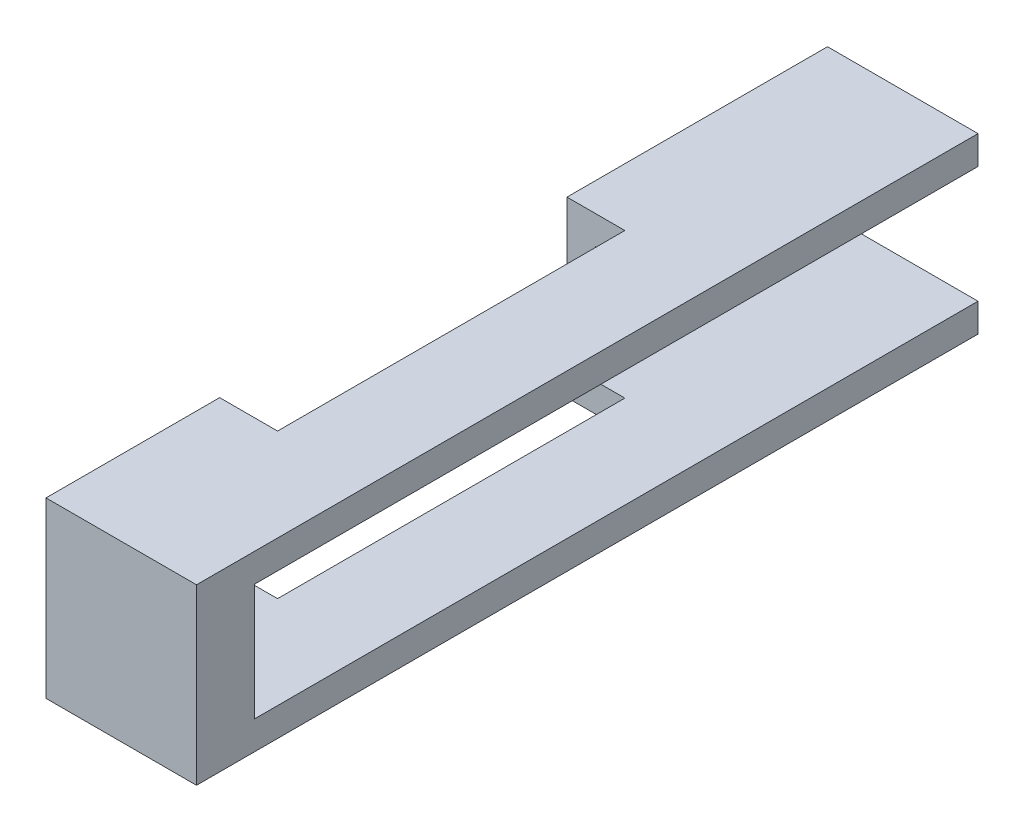
SolidWorks part; units mm, degrees
ref_plane "前视基准面" through (0, 0, 0) normal (0, 0, 1) x (1, 0, 0)
ref_plane "上视基准面" through (0, 0, 0) normal (0, 1, 0) x (1, 0, 0)
ref_plane "右视基准面" through (0, 0, 0) normal (1, 0, 0) x (0, 0, -1)
other "Configuration Table"
sketch "草图1" plane through (0, 0, 0) normal (0, 1, 0) x (1, 0, 0)
  line L1 (-15, 15) -> (15, 15)
  line L2 (-15, 15) -> (-15, -15)
  line L3 (-15, -15) -> (15, -15)
  line L4 (15, 15) -> (15, -15)
  line L5 (-15, 15) -> (15, -15) construction
  line L6 (-15, -15) -> (15, 15) construction
  point P0 (0, 0)
  dimension "D1" = 30
  dimension "D2" = 30
extrude "凸台-拉伸1" add sketch "草图1" along normal blind 30
sketch "草图2" plane through (15, 0, 0) normal (1, 0, 0) x (0, 0, -1)
  line L0 (15, 30) -> (15, 0) construction
  line L1 (-5, 4.975) -> (15, 4.975)
  line L2 (-5, 4.975) -> (-5, 25.025)
  line L3 (-5, 25.025) -> (15, 25.025)
  line L4 (15, 4.975) -> (15, 25.025)
  line L5 (-5, 4.975) -> (15, 25.025) construction
  line L6 (-5, 25.025) -> (15, 4.975) construction
  line L7 (-15, 15) -> (15, 15) construction
  line L9 (-15, 30) -> (-15, 0) construction
  point P0 (5, 15)
  dimension "D1" = 20.05
  dimension "D2" = 20
extrude "切除-拉伸1" cut sketch "草图2" against normal blind 20
sketch "草图3" plane through (-5, 0, 0) normal (1, 0, 0) x (0, 0, -1)
  line L0 (-5, 25.025) -> (15, 4.975)
  line L1 (15, 25.025) -> (-5, 4.975)
  circle A0 centre (5, 15) radius 3.1
  dimension "D1" = 6.2
extrude "切除-拉伸2" cut sketch "草图3" against normal blind 20 contours L0 A0 L1 | L1 A0 L0 | L0 A0 L1 | L1 A0 L0
sketch "草图4" plane through (0, 0, 0) normal (0, -1, 0) x (1, 0, 0)
  line L0 (-10, -15) -> (-10, 15)
  line L4 (15, -15) -> (15, 15)
  line L5 (15, 15) -> (-15, 15)
  line L6 (-15, 15) -> (-15, -15)
  line L7 (-15, -15) -> (15, -15)
  line L8 (15, -15) -> (15, 15)
  line L9 (15, 15) -> (-15, 15)
  line L10 (-15, 15) -> (-15, -15)
  line L11 (-15, -15) -> (15, -15)
  line M7 (15, 15) -> (-15, 15)
  line M8 (-15, 15) -> (-15, -15)
  line M9 (-15, -15) -> (15, -15)
  dimension "D2" = 5
  dimension "D1" = 0
extrude "切除-拉伸3" cut sketch "草图4" against normal blind 55 contours L0 M9 M7 M8
sketch "草图5" plane through (0, 0, -15) normal (0, 0, -1) x (-1, 0, 0)
  line L0 (-15, 30) -> (10, 30) construction
  line L1 (-15, 30) -> (0, 30)
  line L2 (-15, 30) -> (-15, 0)
  line L3 (-15, 0) -> (0, 0)
  line L4 (0, 30) -> (0, 0)
  line L5 (-15, 30) -> (0, 0) construction
  line L6 (-15, 0) -> (0, 30) construction
  line L7 (-15, 0) -> (10, 0) construction
  line L12 (-15, 25.025) -> (-15, 4.975)
  line L13 (-15, 4.975) -> (5, 4.975)
  line L14 (5, 4.975) -> (5, 25.025)
  line L15 (5, 25.025) -> (-15, 25.025)
  line L16 (-15, 25.025) -> (-15, 4.975)
  line L17 (-15, 4.975) -> (5, 4.975)
  line L18 (5, 4.975) -> (5, 25.025)
  line L19 (5, 25.025) -> (-15, 25.025)
  point P0 (-7.5, 15)
  line M6 (-15, 0) -> (10, 0)
  line M8 (10, 30) -> (-15, 30)
  line M9 (-15, 30) -> (-15, 25.025)
  line M10 (-15, 25.025) -> (5, 25.025)
  line M12 (5, 4.975) -> (-15, 4.975)
  line M13 (-15, 4.975) -> (-15, 0)
  dimension "D1" = 15
  dimension "D2" = 0
extrude "凸台-拉伸2" add sketch "草图5" along normal blind 120 contours L4 M8 M9 M10 | L4 M12 M13 M6
sketch "草图6" plane through (0, 0, -135) normal (0, 0, -1) x (-1, 0, 0)
  line L1 (-15, 4.975) -> (5, 4.975)
  line L2 (-15, 4.975) -> (-15, 25.025)
  line L3 (-15, 25.025) -> (5, 25.025)
  line L4 (0, 0) -> (0, 4.975)
  line L5 (0, 4.975) -> (-15, 4.975)
  line L6 (-15, 4.975) -> (-15, 0)
  line L7 (-15, 0) -> (0, 0)
  line L8 (0, 0) -> (0, 4.975)
  line L9 (0, 4.975) -> (-15, 4.975)
  line L10 (-15, 4.975) -> (-15, 0)
  line L11 (-15, 0) -> (0, 0)
  line L12 (0, 25.025) -> (0, 30)
  line L13 (0, 30) -> (-15, 30)
  line L14 (-15, 30) -> (-15, 25.025)
  line L15 (-15, 25.025) -> (0, 25.025)
  line L16 (0, 25.025) -> (0, 30)
  line L17 (0, 30) -> (-15, 30)
  line L18 (-15, 30) -> (-15, 25.025)
  line L19 (-15, 25.025) -> (0, 25.025)
  line L20 (5, 4.975) -> (5, 25.025)
  line L21 (-15, 4.975) -> (5, 25.025) construction
  line L22 (-15, 25.025) -> (5, 4.975) construction
  line L23 (-15, 0) -> (10, 0)
  line L24 (-15, 0) -> (-15, 30)
  line L25 (-15, 30) -> (10, 30)
  line L26 (10, 0) -> (10, 30)
  line L27 (-15, 0) -> (10, 30) construction
  line L28 (-15, 30) -> (10, 0) construction
  point P6 (-5, 15)
  point P10 (-2.5, 15)
  line M11 (0, 0) -> (0, 4.975)
  dimension "D3" = 20
  dimension "D4" = 25
  dimension "D1" = 0
  dimension "D2" = 0
extrude "凸台-拉伸3" add sketch "草图6" against normal blind 60 contours L23 L26 L25 L16 L3 L20 L1 M11
sketch "草图7" plane through (-10, 0, 0) normal (-1, 0, 0) x (0, 0, 1)
  circle A0 centre (-85, 15) radius 5.25 construction
  circle A1 centre (-105, 15) radius 5.25 construction
  circle A2 centre (-85, 15) radius 5.25
  circle A3 centre (-105, 15) radius 5.25
  circle A4 centre (-105, 15) radius 3.1
  circle A5 centre (-85, 15) radius 3.1
  circle A6 centre (-5, 15) radius 3.1 construction
extrude "切除-拉伸4" cut sketch "草图7" against normal blind 60 contours A4 | A5
sketch "草图8" plane through (0, 0, -135) normal (0, 0, -1) x (-1, 0, 0)
  line L8 (-15.05, 25.075) -> (-15.05, 4.925)
  line L9 (-15.05, 4.925) -> (5.05, 4.925)
  line L10 (5.05, 4.925) -> (5.05, 25.075)
  line L11 (5.05, 25.075) -> (-15.05, 25.075)
  line L12 (-15.05, 25.075) -> (-15.05, 4.925)
  line L13 (-15.05, 4.925) -> (5.05, 4.925)
  line L14 (5.05, 4.925) -> (5.05, 25.075)
  line L15 (5.05, 25.075) -> (-15.05, 25.075)
  dimension "D1" = 0.05
extrude "切除-拉伸5" cut sketch "草图8" against normal up to surface (140 mm away) up to face at (5, 15, 5)
sketch "草图9" plane through (15, 0, 0) normal (1, 0, 0) x (0, 0, -1)
  line L8 (135, 4.925) -> (-5, 4.925)
  line L9 (-5, 4.925) -> (-5, 25.075)
  line L10 (-5, 25.075) -> (135, 25.075)
  line L11 (135, 25.075) -> (135, 30)
  line L12 (135, 30) -> (-15, 30)
  line L13 (-15, 30) -> (-15, 0)
  line L14 (-15, 0) -> (135, 0)
  line L15 (135, 0) -> (135, 4.925)
  line L16 (135, 4.925) -> (-5, 4.925)
  line L17 (-5, 4.925) -> (-5, 25.075)
  line L18 (-5, 25.075) -> (135, 25.075)
  line L19 (135, 25.075) -> (135, 30)
  line L20 (135, 30) -> (-15, 30)
  line L21 (-15, 30) -> (-15, 0)
  line L22 (-15, 0) -> (135, 0)
  line L23 (135, 0) -> (135, 4.925)
  dimension "D1" = 0
extrude "凸台-拉伸4" add sketch "草图9" along normal blind 1
sketch "草图10" plane through (0, 0, 0) normal (0, -1, 0) x (1, 0, 0)
  line L0 (-10, -120) -> (16, -120)
  line L8 (16, 15) -> (-10, 15)
  line L9 (-10, 15) -> (-10, -15)
  line L10 (-10, -15) -> (0, -15)
  line L11 (0, -15) -> (0, -75)
  line L12 (0, -75) -> (-10, -75)
  line L13 (-10, -75) -> (-10, -135)
  line L14 (-10, -135) -> (16, -135)
  line L15 (16, -135) -> (16, 15)
  line L16 (16, 15) -> (-10, 15)
  line L17 (-10, 15) -> (-10, -15)
  line L18 (-10, -15) -> (0, -15)
  line L19 (0, -15) -> (0, -75)
  line L20 (0, -75) -> (-10, -75)
  line L21 (-10, -75) -> (-10, -135)
  line L22 (-10, -135) -> (16, -135)
  line L23 (16, -135) -> (16, 15)
  line M15 (-10, -75) -> (-10, -135)
  line M16 (-10, -135) -> (16, -135)
  line M17 (16, -135) -> (16, 15)
  dimension "D2" = 15
  dimension "D1" = 0
extrude "切除-拉伸6" cut sketch "草图10" against normal blind 87 contours L0 M15 M16 M17
